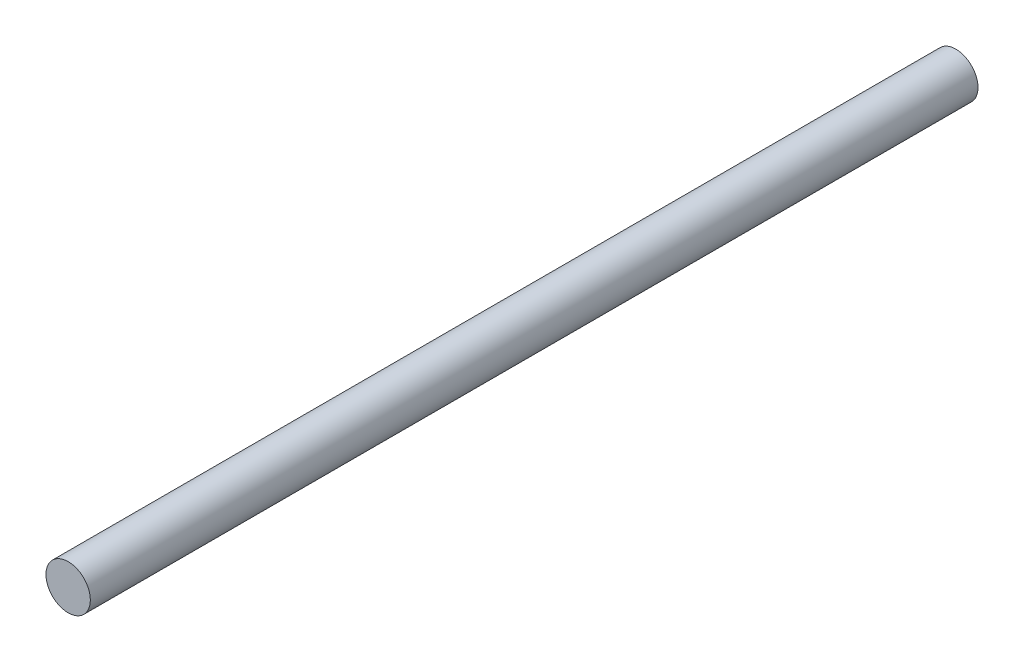
SolidWorks part; units mm, degrees
ref_plane "Plan de face" through (0, 0, 0) normal (0, 0, 1) x (1, 0, 0)
ref_plane "Plan de dessus" through (0, 0, 0) normal (0, 1, 0) x (1, 0, 0)
ref_plane "Plan de droite" through (0, 0, 0) normal (1, 0, 0) x (0, 0, -1)
sketch "Esquisse1" plane through (0, 0, 0) normal (0, 0, 1) x (1, 0, 0)
  circle A0 centre (0, 0) radius 2.5
  dimension "D1" = 5
extrude "Boss.-Extru.1" add sketch "Esquisse1" along normal blind 100
